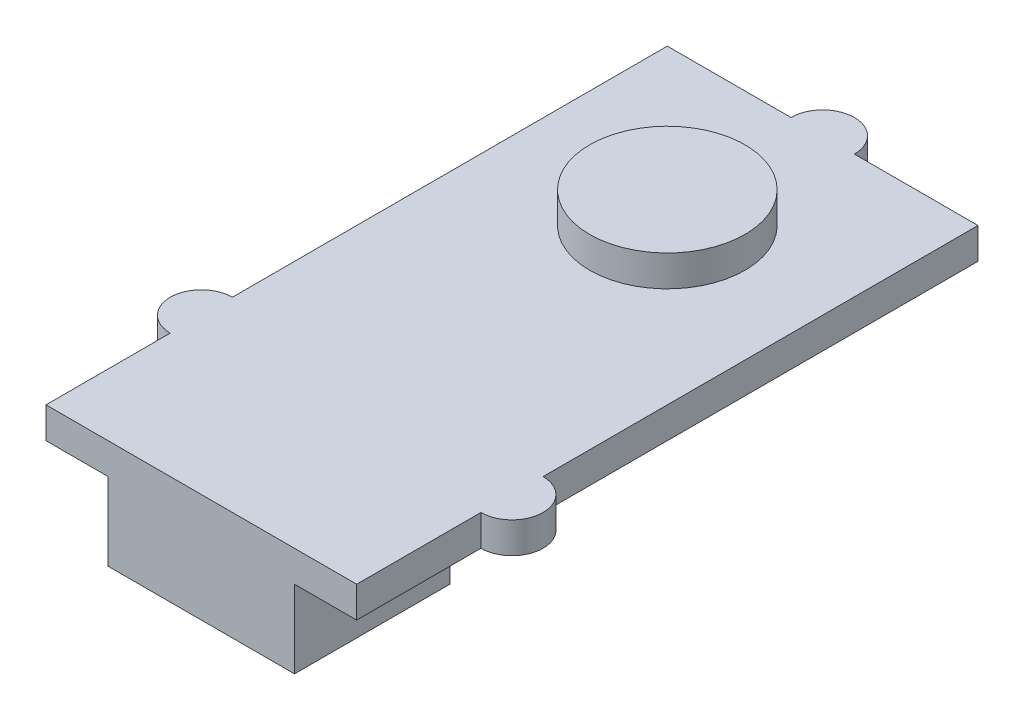
SolidWorks part; units mm, degrees
ref_plane "Front" through (0, 0, 0) normal (0, 0, 1) x (1, 0, 0)
ref_plane "Top" through (0, 0, 0) normal (0, 1, 0) x (1, 0, 0)
ref_plane "Right" through (0, 0, 0) normal (1, 0, 0) x (0, 0, -1)
sketch "Sketch2" plane through (0, 0, 0) normal (0, 1, 0) x (1, 0, 0)
  line L0 (2.0433, 20) -> (10, 20)
  line L1 (-10, 20) -> (-2.0433, 20)
  line L2 (-10, 20) -> (-10, -8)
  line L3 (-10, -20) -> (10, -20)
  line L4 (10, 20) -> (10, -8)
  line L5 (-10, 20) -> (10, -20) construction
  line L6 (-10, -20) -> (10, 20) construction
  line L9 (10, -12) -> (10, -20)
  line L10 (-10, -12) -> (-10, -20)
  arc A0 (2.0433, 20) -> (-2.0433, 20) centre (0, 20) ccw
  arc A1 (-10, -8) -> (-10, -12) centre (-10, -10) ccw
  arc A2 (10, -12) -> (10, -8) centre (10, -10) ccw
  point P0 (0, 0)
extrude "Boss-Extrude1" add sketch "Sketch2" along normal blind 2
sketch "Sketch3" plane through (0, 2, 0) normal (0, 1, 0) x (1, 0, 0)
  circle A1 centre (0, 10) radius 5
extrude "Boss-Extrude2" add sketch "Sketch3" along normal blind 2
sketch "Sketch5" plane through (0, 0, 0) normal (0, -1, 0) x (1, 0, 0)
  line L1 (-10, 20) -> (10, 20) construction
  line L3 (6, 20) -> (-6, 20)
  line L4 (6, 20) -> (6, 10)
  line L5 (6, 10) -> (-6, 10)
  line L6 (-6, 20) -> (-6, 10)
  dimension "D2" = 12
extrude "Boss-Extrude3" add sketch "Sketch5" along normal blind 5
